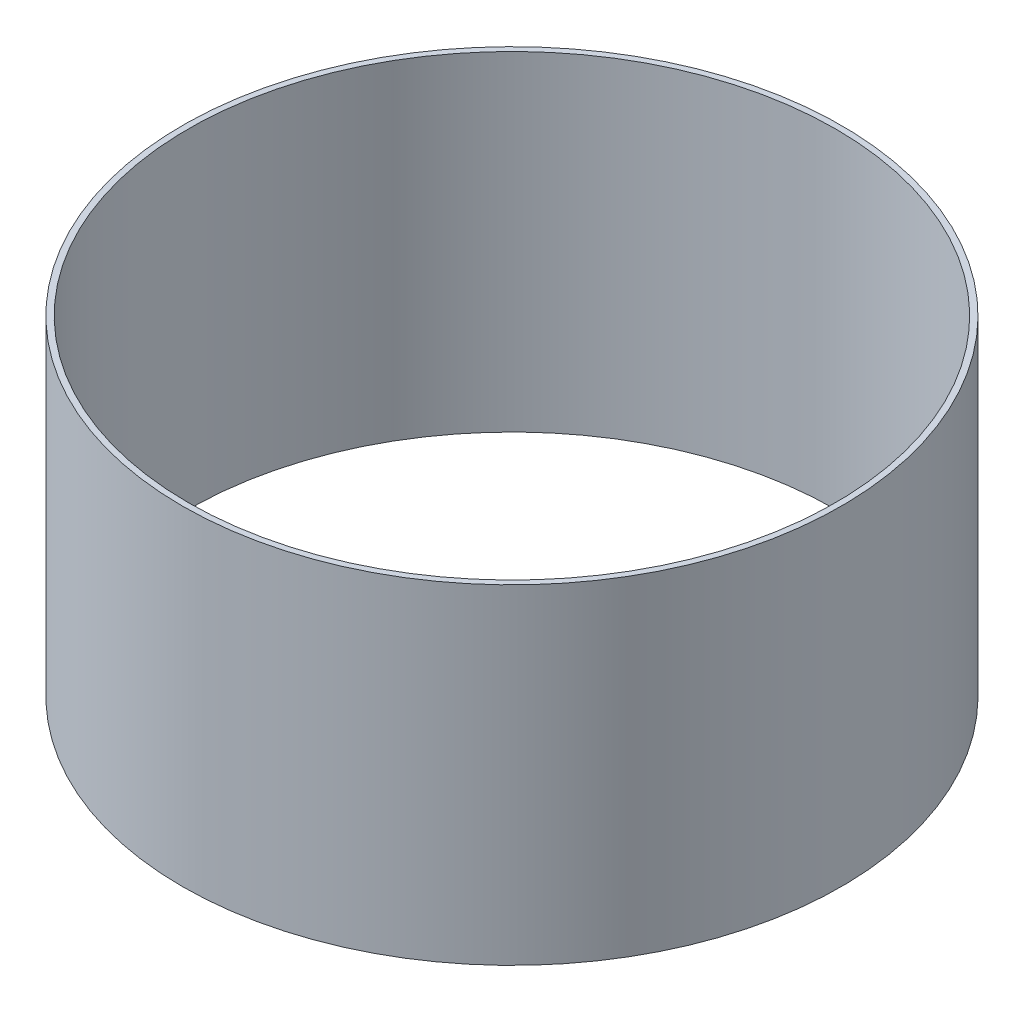
SolidWorks part; units mm, degrees
ref_plane "正面" through (0, 0, 0) normal (0, 0, 1) x (1, 0, 0)
ref_plane "平面" through (0, 0, 0) normal (0, 1, 0) x (1, 0, 0)
ref_plane "右側面" through (0, 0, 0) normal (1, 0, 0) x (0, 0, -1)
sketch "ｽｹｯﾁ1" plane through (0, 0, 0) normal (0, 1, 0) x (1, 0, 0)
  circle A0 centre (0, 0) radius 13.75
  circle A1 centre (0, 0) radius 14
  dimension "D1" = 27.5
  dimension "D2" = 28
extrude "ﾎﾞｽ - 押し出し1" add sketch "ｽｹｯﾁ1" along normal blind 14
